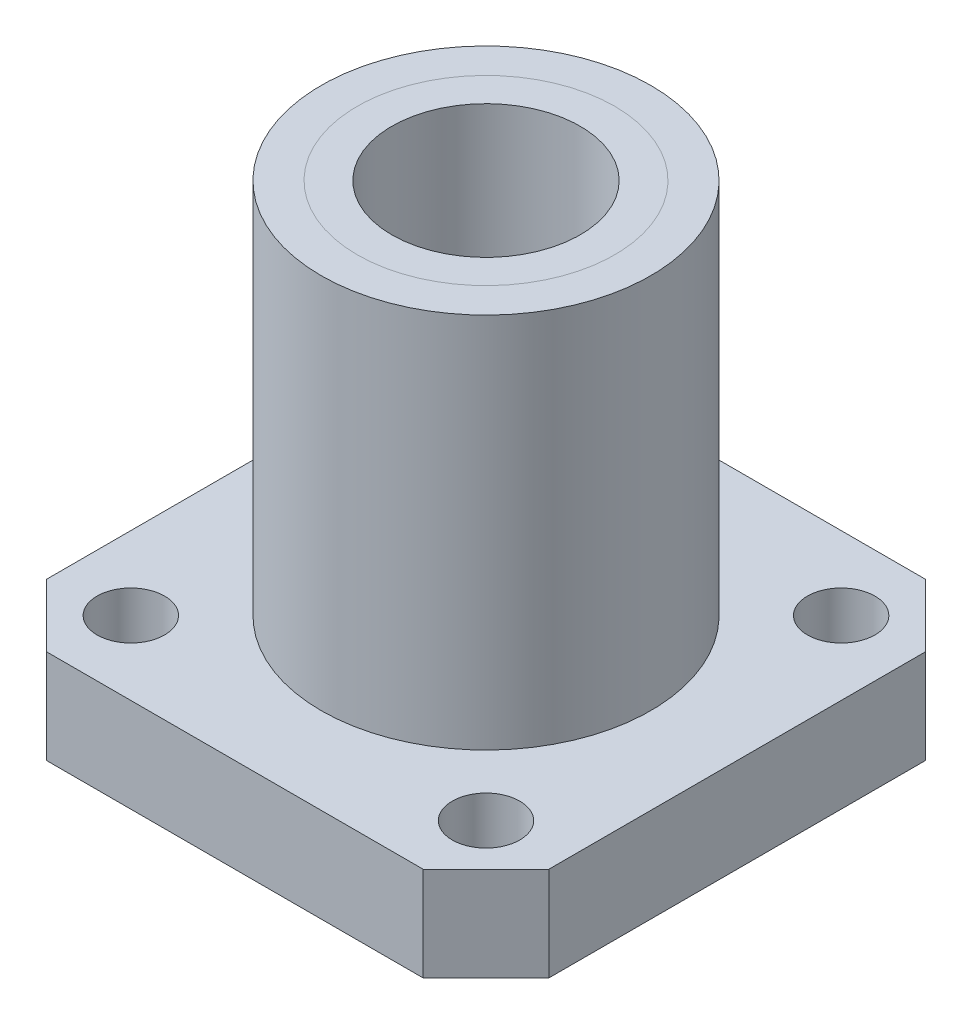
SolidWorks part; units mm, degrees
ref_plane "Front Plane" through (0, 0, 0) normal (0, 0, 1) x (1, 0, 0)
ref_plane "Top Plane" through (0, 0, 0) normal (0, 1, 0) x (1, 0, 0)
ref_plane "Right Plane" through (0, 0, 0) normal (1, 0, 0) x (0, 0, -1)
sketch "Sketch1" plane through (0, 0, 0) normal (0, 1, 0) x (1, 0, 0)
  circle A0 centre (0, 0) radius 10.5
  circle A1 centre (0, 0) radius 6
  dimension "D1" = 21
  dimension "D2" = 12
extrude "Boss-Extrude1" add sketch "Sketch1" along normal blind 30
sketch "Sketch2" plane through (0, 0, 0) normal (0, 1, 0) x (1, 0, 0)
  line L1 (-16, 16) -> (16, 16)
  line L2 (-16, 16) -> (-16, -16)
  line L3 (-16, -16) -> (16, -16)
  line L4 (16, 16) -> (16, -16)
  line L5 (-16, 16) -> (16, -16) construction
  line L6 (-16, -16) -> (16, 16) construction
  circle A0 centre (0, 0) radius 14.1471 construction
  circle A1 centre (0, 0) radius 6
  point P0 (0, 0)
  dimension "D3" = 12
  dimension "D1" = 32
  dimension "D2" = 32
extrude "Boss-Extrude2" add sketch "Sketch2" along normal blind 6
sketch "Sketch3" plane through (0, 0, 0) normal (0, 1, 0) x (1, 0, 0)
  line L1 (-11.3137, 11.3137) -> (11.3137, 11.3137) construction
  line L2 (-11.3137, 11.3137) -> (-11.3137, -11.3137) construction
  line L3 (-11.3137, -11.3137) -> (11.3137, -11.3137) construction
  line L4 (11.3137, 11.3137) -> (11.3137, -11.3137) construction
  line L5 (-11.3137, 11.3137) -> (11.3137, -11.3137) construction
  line L6 (-11.3137, -11.3137) -> (11.3137, 11.3137) construction
  circle A0 centre (-11.3137, 11.3137) radius 2.15
  circle A1 centre (-11.3137, -11.3137) radius 2.15
  circle A2 centre (11.3137, -11.3137) radius 2.15
  circle A3 centre (11.3137, 11.3137) radius 2.15
  circle A4 centre (0, 0) radius 16 construction
  point P0 (0, 0)
  dimension "D2" = 32
  dimension "D1" = 4.3
extrude "Cut-Extrude1" cut sketch "Sketch3" along normal through all
chamfer "Chamfer1" distance 4 angle 45 4 edges at (16, 3, -16) (16, 3, 16) (-16, 3, 16) (-16, 3, -16)
sketch "Sketch4" plane through (0, 0, 0) normal (0, 1, 0) x (1, 0, 0)
  circle A0 centre (0, 0) radius 8.2
  circle A1 centre (0, 0) radius 6 construction
  dimension "D1" = 2.2
split line "Split Line1"
equation "\"dmin\"= 12"
equation "\"dmax\"= 21"
equation "\"l\"= 30"
equation "\"k\"= 32"
equation "\"b\"= 6"
equation "\"holespace\"= 32"
equation "\"holes\"= 4.3"
equation "\"D1@Boss-Extrude1\"=\"l\""
equation "\"D2@Sketch1\"=\"dmin\""
equation "\"D1@Sketch1\"=\"dmax\""
equation "\"D3@Sketch2\"=\"dmin\""
equation "\"D1@Sketch2\"=\"k\""
equation "\"D2@Sketch2\"=\"k\""
equation "\"D1@Boss-Extrude2\"=\"b\""
equation "\"D2@Sketch3\"=\"holespace\""
equation "\"D1@Sketch3\"=\"holes\""
equation "\"chamfer\" = 4"
equation "\"D1@Chamfer1\"=\"chamfer\""
